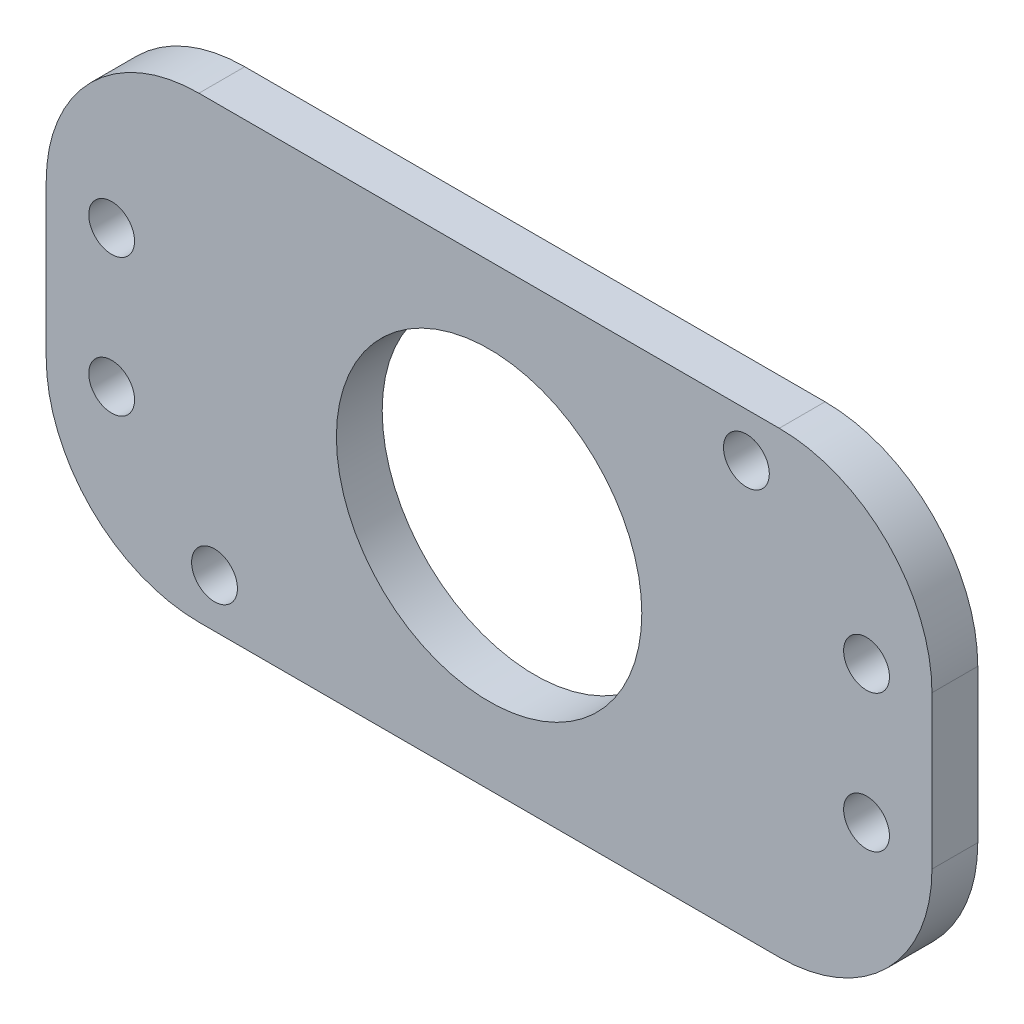
SolidWorks part; units mm, degrees
ref_plane "Front Plane" through (0, 0, 0) normal (0, 0, 1) x (1, 0, 0)
ref_plane "Top Plane" through (0, 0, 0) normal (0, 1, 0) x (1, 0, 0)
ref_plane "Right Plane" through (0, 0, 0) normal (1, 0, 0) x (0, 0, -1)
sketch "Sketch1" plane through (0, 0, 0) normal (0, 0, 1) x (1, 0, 0)
  line L1 (-36.3458, 17.1021) -> (21.6542, 17.1021)
  line L2 (-36.3458, 17.1021) -> (-36.3458, 47.1021)
  line L3 (-36.3458, 47.1021) -> (21.6542, 47.1021)
  line L4 (21.6542, 17.1021) -> (21.6542, 47.1021)
  line L5 (-36.3458, 17.1021) -> (21.6542, 47.1021) construction
  line L6 (-36.3458, 47.1021) -> (21.6542, 17.1021) construction
  point P0 (-7.3458, 32.1021)
  dimension "D1" = 30
  dimension "D2" = 58
extrude "Boss-Extrude1" add sketch "Sketch1" along normal blind 3
fillet "Fillet1" radius 10 4 edges at (21.6542, 47.1021, 1.5) (21.6542, 17.1021, 1.5) (-36.3458, 47.1021, 1.5) (-36.3458, 17.1021, 1.5)
ref_plane "Plane1" through (-7.3458, 0, 0) normal (1, 0, 0) x (0, 0, -1)
sketch "Sketch2" plane through (0, 0, 3) normal (0, 0, 1) x (1, 0, 0)
  circle A0 centre (17.3692, 27.6021) radius 1.5
  circle A1 centre (17.3692, 36.6021) radius 1.5
  dimension "D1" = 3
  dimension "D2" = 3
extrude "Cut-Extrude1" cut sketch "Sketch2" against normal blind 3
mirror "Mirror1" about plane through (-7.3458, 0, 0) normal (1, 0, 0) of "Cut-Extrude1"
sketch "Sketch3" plane through (0, 0, 3) normal (0, 0, 1) x (1, 0, 0)
  circle A0 centre (-25.3264, 20.2717) radius 1.5
  circle A1 centre (9.5035, 44.1944) radius 1.5
  dimension "D1" = 3
  dimension "D2" = 3
extrude "Cut-Extrude2" cut sketch "Sketch3" against normal blind 3
sketch "Sketch4" plane through (0, 0, 3) normal (0, 0, 1) x (1, 0, 0)
  line L0 (-36.3458, 32.1021) -> (21.6542, 32.1021) construction
  line L1 (-36.3458, 37.1021) -> (-36.3458, 27.1021) construction
  line L2 (21.6542, 27.1021) -> (21.6542, 37.1021) construction
  line L3 (-7.3458, 47.1021) -> (-7.3458, 17.1021) construction
  line L4 (11.6542, 47.1021) -> (-26.3458, 47.1021) construction
  line L5 (-26.3458, 17.1021) -> (11.6542, 17.1021) construction
  circle A0 centre (-7.3458, 32.1021) radius 10
  dimension "D1" = 20
extrude "Cut-Extrude3" cut sketch "Sketch4" against normal blind 10
